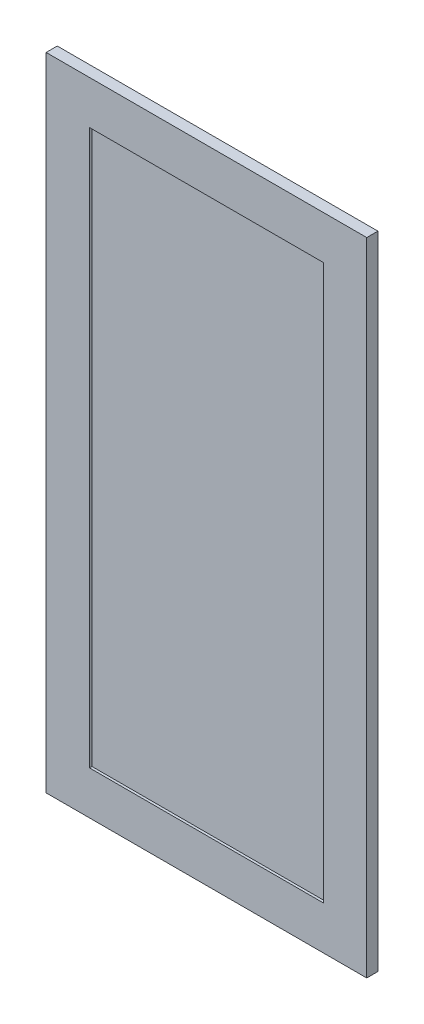
SolidWorks part; units mm, degrees
material "Pine"
ref_plane "Front Plane" through (0, 0, 0) normal (0, 0, 1) x (1, 0, 0)
ref_plane "Top Plane" through (0, 0, 0) normal (0, 1, 0) x (1, 0, 0)
ref_plane "Right Plane" through (0, 0, 0) normal (1, 0, 0) x (0, 0, -1)
sketch "Sketch1" plane through (0, 0, 0) normal (0, 0, 1) x (1, 0, 0)
  line L1 (-259, 518) -> (259, 518)
  line L2 (-259, 518) -> (-259, -518)
  line L3 (-259, -518) -> (259, -518)
  line L4 (259, 518) -> (259, -518)
  line L5 (-259, 518) -> (259, -518) construction
  line L6 (-259, -518) -> (259, 518) construction
  point P0 (0, 0)
  dimension "D1" = 1036
  dimension "D2" = 518
extrude "Boss-Extrude1" add sketch "Sketch1" along normal blind 18
sketch "Sketch2" plane through (0, 0, 18) normal (0, 0, 1) x (1, 0, 0)
  line L0 (-259, 518) -> (-259, -518) construction
  line L1 (-189, 448) -> (189, 448)
  line L2 (-189, 448) -> (-189, -448)
  line L3 (-189, -448) -> (189, -448)
  line L4 (189, 448) -> (189, -448)
  line L5 (-189, 448) -> (189, -448) construction
  line L6 (-189, -448) -> (189, 448) construction
  line L7 (259, 518) -> (-259, 518) construction
  point P0 (0, 0)
  dimension "D1" = 70
  dimension "D2" = 70
extrude "Cut-Extrude1" cut sketch "Sketch2" against normal blind 4
